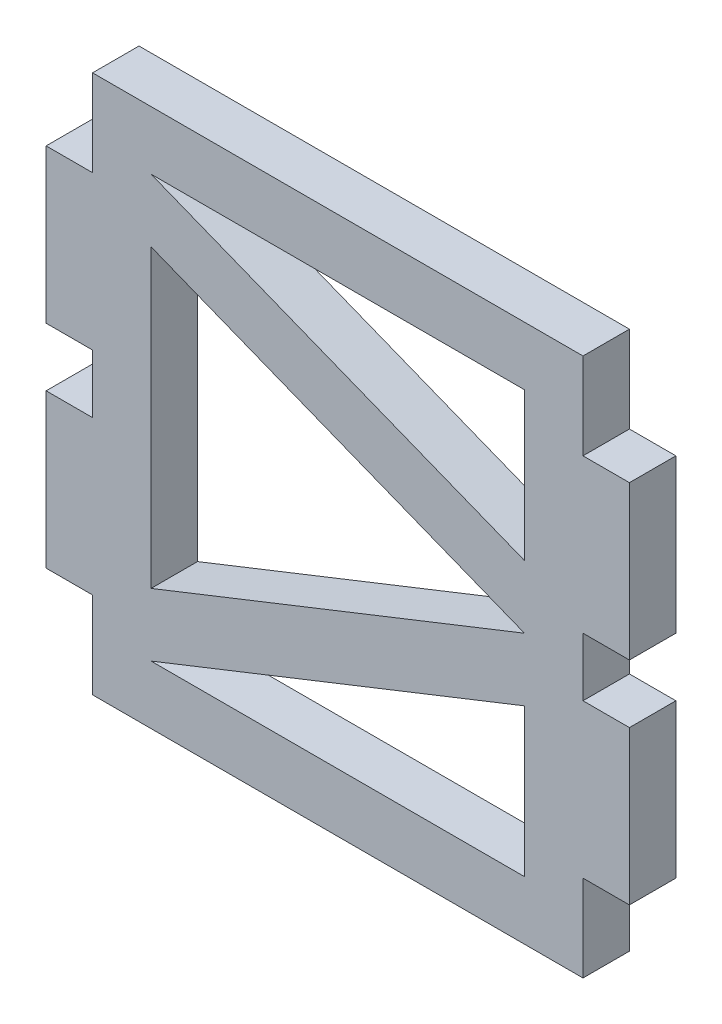
SolidWorks part; units mm, degrees
material "Birch Plywood"
ref_plane "Front Plane" through (0, 0, 0) normal (0, 0, 1) x (1, 0, 0)
ref_plane "Top Plane" through (0, 0, 0) normal (0, 1, 0) x (1, 0, 0)
ref_plane "Right Plane" through (0, 0, 0) normal (1, 0, 0) x (0, 0, -1)
sketch "Sketch1" plane through (0, 0, 0) normal (0, 0, 1) x (1, 0, 0)
  line L0 (3.175, 27.5) -> (0, 27.5) construction
  line L1 (0, 27.5) -> (0, 38) construction
  line L2 (3.175, 38) -> (0, 38) construction
  line L3 (3.175, 42) -> (0, 42) construction
  line L4 (0, 42) -> (0, 52.5) construction
  line L5 (3.175, 52.5) -> (0, 52.5) construction
  line L6 (36.7, 27.5) -> (39.875, 27.5) construction
  line L7 (39.875, 27.5) -> (39.875, 38) construction
  line L8 (36.7, 38) -> (39.875, 38) construction
  line L9 (36.7, 42) -> (39.875, 42) construction
  line L10 (39.875, 42) -> (39.875, 52.5) construction
  line L11 (36.7, 52.5) -> (39.875, 52.5) construction
  line L12 (3.175, 27.5) -> (0, 27.5)
  line L13 (0, 27.5) -> (0, 38)
  line L14 (3.175, 38) -> (0, 38)
  line L15 (3.175, 42) -> (0, 42)
  line L16 (0, 42) -> (0, 52.5)
  line L17 (3.175, 52.5) -> (0, 52.5)
  line L18 (36.7, 27.5) -> (39.875, 27.5)
  line L19 (39.875, 27.5) -> (39.875, 38)
  line L20 (36.7, 38) -> (39.875, 38)
  line L21 (36.7, 42) -> (39.875, 42)
  line L22 (39.875, 42) -> (39.875, 52.5)
  line L23 (36.7, 52.5) -> (39.875, 52.5)
  line L24 (39.875, 42) -> (39.875, 38) construction
  line L25 (0, 42) -> (0, 38) construction
  line L26 (0, 40) -> (39.875, 40) construction
  line L27 (36.7, 42) -> (36.7, 38)
  line L28 (3.175, 42) -> (3.175, 38)
  line L29 (36.7, 52.5) -> (36.7, 58.4125)
  line L30 (36.7, 58.4125) -> (3.175, 58.4125)
  line L31 (3.175, 58.4125) -> (3.175, 52.5)
  line L32 (36.7, 27.5) -> (36.7, 21.5875)
  line L33 (36.7, 21.5875) -> (3.175, 21.5875)
  line L34 (3.175, 21.5875) -> (3.175, 27.5)
  line L35 (32.7, 40) -> (7.175, 50.1102)
  line L36 (7.175, 50.1102) -> (7.175, 29.8898)
  line L37 (7.175, 29.8898) -> (32.7, 40)
  line L38 (32.7, 54.4125) -> (7.175, 54.4125)
  line L39 (7.175, 54.4125) -> (32.7, 44.3023)
  line L40 (32.7, 44.3023) -> (32.7, 54.4125)
  line L41 (32.7, 25.5875) -> (32.7, 35.6977)
  line L42 (32.7, 35.6977) -> (7.175, 25.5875)
  line L43 (7.175, 25.5875) -> (32.7, 25.5875)
  line L44 (3.175, 21.5875) -> (0, 21.5875) construction
  line L45 (0, 58.4125) -> (3.175, 58.4125) construction
  line L46 (3.175, 21.5875) -> (0, 21.5875) construction
  line L47 (0, 58.4125) -> (3.175, 58.4125) construction
  dimension "D1" = 4
  dimension "D2" = 4
  dimension "D3" = 4
  dimension "D4" = 4
  dimension "D5" = 4
extrude "Boss-Extrude1" add sketch "Sketch1" along normal up to surface (3.175 mm away)
